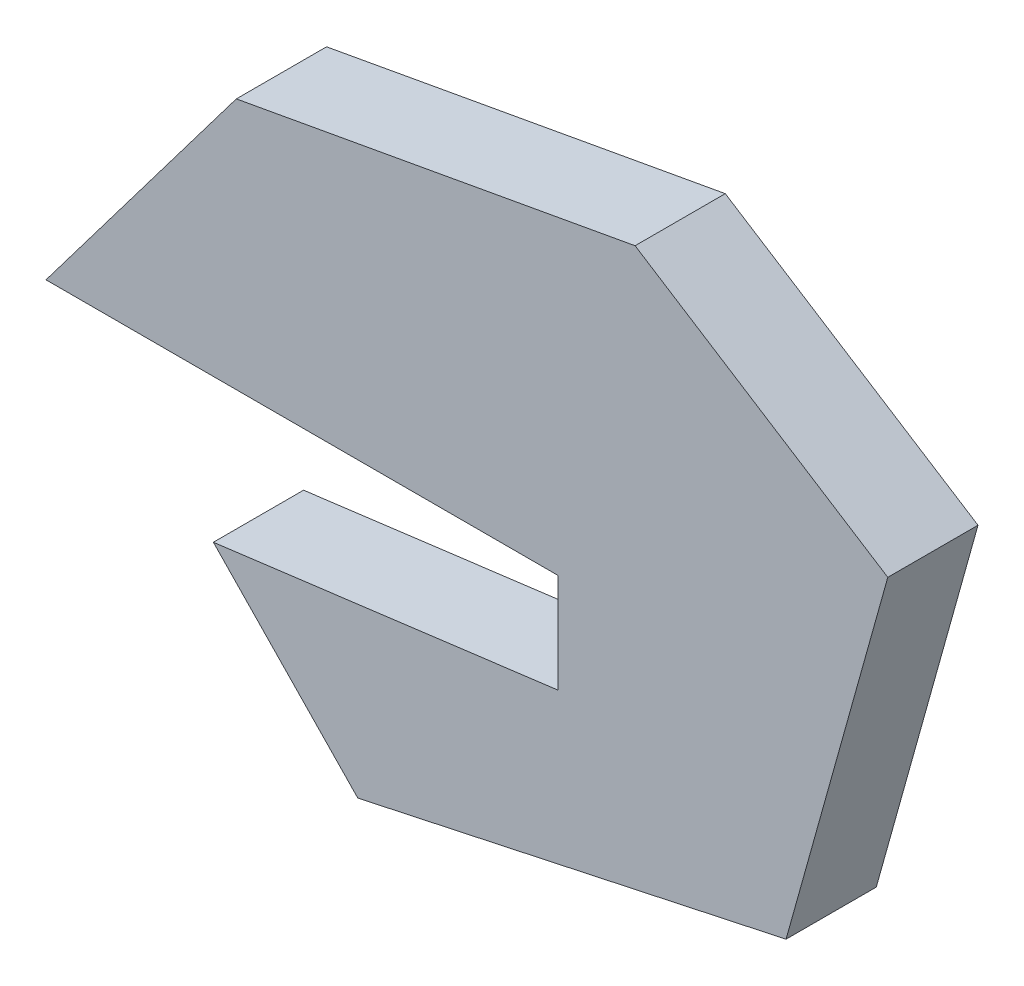
SolidWorks part; units mm, degrees
ref_plane "Front Plane" through (0, 0, 0) normal (0, 0, 1) x (1, 0, 0)
ref_plane "Top Plane" through (0, 0, 0) normal (0, 1, 0) x (1, 0, 0)
ref_plane "Right Plane" through (0, 0, 0) normal (1, 0, 0) x (0, 0, -1)
sketch "Sketch1" plane through (0, 0, 0) normal (0, 0, 1) x (1, 0, 0)
  line L0 (0, 0) -> (-113.5128, 0)
  line L1 (-113.5128, 0) -> (-71.3093, 55.8468)
  line L2 (-71.3093, 55.8468) -> (17.0997, 71.855)
  line L3 (17.0997, 71.855) -> (73.1284, 36.2004)
  line L4 (73.1284, 36.2004) -> (50.5714, -44.5683)
  line L5 (50.5714, -44.5683) -> (-44.3864, -64.9424)
  line L6 (-44.3864, -64.9424) -> (-76.4028, -31.8345)
  line L7 (-76.4028, -31.8345) -> (0, -22.0193)
  line L8 (0, -22.0193) -> (0, 0)
  dimension "D1" = 70
  dimension "D2" = 88.409
extrude "Boss-Extrude1" add sketch "Sketch1" along normal blind 20
